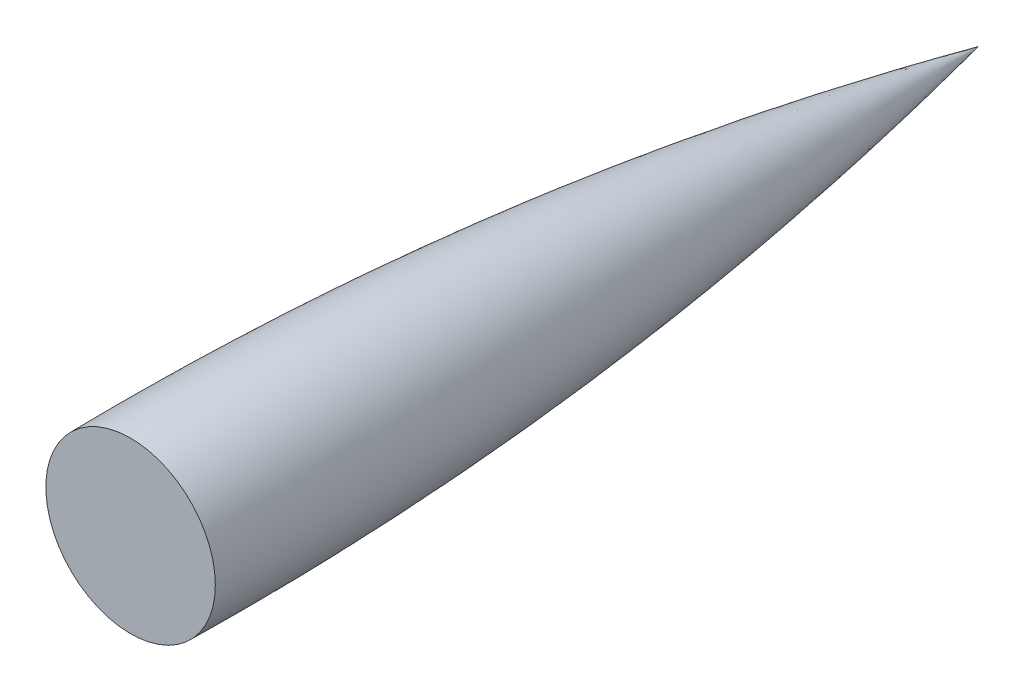
SolidWorks part; units mm, degrees
ref_plane "Front Plane" through (0, 0, 0) normal (0, 0, 1) x (1, 0, 0)
ref_plane "Top Plane" through (0, 0, 0) normal (0, 1, 0) x (1, 0, 0)
ref_plane "Right Plane" through (0, 0, 0) normal (1, 0, 0) x (0, 0, -1)
sketch "Sketch1" plane through (0, 0, 0) normal (0, 1, 0) x (1, 0, 0)
  line L0 (0, 0) -> (50.8, 0)
  line L1 (0, 0) -> (0, 508)
  arc A0 (0, 508) -> (50.8, 0) centre (-2220.9039, 29.3696) cw
  dimension "D1" = 50.8
  dimension "D2" = 508
revolve "Revolve2" add sketch "Sketch1" angle 360 about L1
